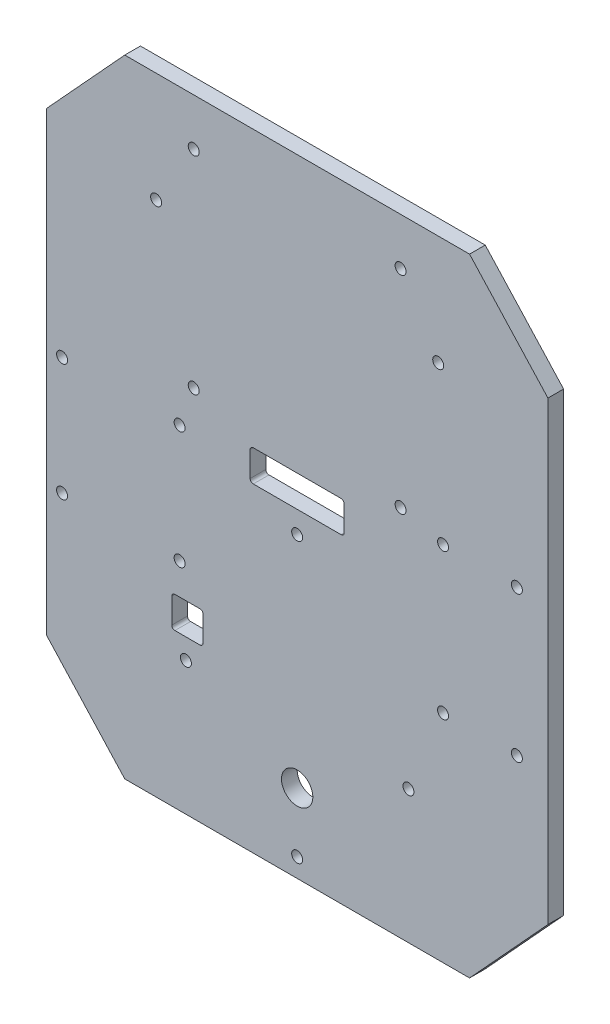
SolidWorks part; units mm, degrees
ref_plane "Plan de face" through (0, 0, 0) normal (1, 0, 0) x (0, 1, 0)
ref_plane "Plan de dessus" through (0, 0, 0) normal (0, 0, 1) x (0, 1, 0)
ref_plane "Plan de droite" through (0, 0, 0) normal (0, 1, 0) x (-1, 0, 0)
sketch "Esquisse1" plane through (0, 0, 0) normal (0, 0, 1) x (0, 1, 0)
  line L0 (0, 0) -> (-150.5414, 0) construction
  line L1 (-100, -80) -> (100, -80)
  line L2 (-100, -80) -> (-100, 80)
  line L3 (-100, 80) -> (100, 80)
  line L5 (-100, -80) -> (100, 80) construction
  line L6 (-100, 80) -> (100, -80) construction
  line L12 (-31, 38.8179) -> (-31, 42.3315) construction
  line L13 (-51, 40) -> (-41, 40)
  line L17 (-51, 40) -> (-51, 30)
  line L18 (-51, 30) -> (-41, 30)
  line L19 (-41, 40) -> (-41, 30)
  line L21 (-31.059, 37.5) -> (-30.571, 37.5) construction
  line L22 (-31, -46.5413) -> (-34.2714, -46.5413) construction
  line L28 (100, 80) -> (100, -80)
  line L30 (2, 15) -> (12, 15)
  line L31 (2, 15) -> (2, -15)
  line L32 (2, -15) -> (12, -15)
  line L33 (12, 15) -> (12, -15)
  circle A0 centre (-75, 0) radius 5
  circle A1 centre (-57.5, 35.5) radius 1.75
  circle A2 centre (-57.5, -35.5) radius 1.75
  circle A3 centre (65, 45) radius 1.75
  circle A4 centre (65, -45) radius 1.75
  circle A5 centre (-31, 37.5) radius 1.75
  circle A6 centre (-31, 75) radius 1.75
  circle A7 centre (6.5, 75) radius 1.75
  circle A8 centre (6.5, 37.5) radius 1.75
  circle A9 centre (-31, -46.5413) radius 1.75
  circle A10 centre (-31, -70.0913) radius 1.75
  circle A11 centre (15.5, -46.5413) radius 1.75
  circle A12 centre (15.5, -70.0913) radius 1.75
  circle A13 centre (-4.9993, 0) radius 1.75
  circle A16 centre (85, 33) radius 1.75
  circle A17 centre (85.0012, -33) radius 1.75
  circle A18 centre (19, 33) radius 1.75
  circle A19 centre (19.0012, -33) radius 1.75
  point P0 (0, 0)
  dimension "D3" = 10
  dimension "D9" = 3.5
  dimension "D10" = 35.5
  dimension "D11" = 17.5
  dimension "D5" = 3.5
  dimension "D6" = 45
  dimension "D7" = 15
  dimension "D16" = 37.5
  dimension "D17" = 37.5
  dimension "D18" = 37.5
  dimension "D19" = 3.5
  dimension "D20" = 3.5
  dimension "D21" = 3.5
  dimension "D22" = 3.5
  dimension "D23" = 10
  dimension "D24" = 5
  dimension "D25" = 3.5
  dimension "D26" = 3.5
  dimension "D27" = 3.5
  dimension "D28" = 3.5
  dimension "D29" = 46.5
  dimension "D30" = 46.5
  dimension "D31" = 23.55
  dimension "D32" = 23.55
  dimension "D35" = 3.5
  dimension "D36" = 3.5
  dimension "D41" = 66
  dimension "D42" = 66
  dimension "D47" = 3.5
  dimension "D48" = 3.5
  dimension "D50" = 66
  dimension "D52" = 33
  dimension "D33" = 14.9988
  dimension "D34" = 3.5
  dimension "D40" = 66
  dimension "D1" = 200
  dimension "D2" = 160
  dimension "D4" = 25
  dimension "D8" = 6.5
  dimension "D12" = 10
  dimension "D13" = 10
  dimension "D14" = 40
  dimension "D15" = 37.5
  dimension "D37" = 15
  dimension "D38" = 15
  dimension "D39" = 10
  dimension "D43" = 102
extrude "Boss.-Extru.1" add sketch "Esquisse1" along normal blind 5
fillet "Congé2" radius 1 8 edges at (-30, -51, 2.5) (-30, -41, 2.5) (-40, -41, 2.5) (-40, -51, 2.5) (15, 2, 2.5) (15, 12, 2.5) (-15, 12, 2.5) (-15, 2, 2.5)
sketch "Esquisse2" plane through (0, 0, 5) normal (0, 0, 1) x (1, 0, 0)
  line L0 (-110, 40) -> (0, 160)
  line L1 (0, 160) -> (110, 40)
  line L2 (110, 40) -> (110, -40)
  line L3 (110, -40) -> (0, -160)
  line L5 (0, -160) -> (-110, -40)
  line L6 (-110, -40) -> (-110, 40)
  line L14 (-573.5804, 598.1671) -> (-698.6982, -488.0825)
  line L15 (-80, 100) -> (-80, -100) construction
  line L16 (80, -100) -> (80, 100) construction
  line L17 (0, 70) -> (0, 33.5097) construction
  line L18 (-698.6982, -488.0825) -> (684.3, -647.3807)
  line L19 (0, 0) -> (-114.7759, 0) construction
  line L20 (684.3, -647.3807) -> (762.9047, 702.4319)
  line L21 (762.9047, 702.4319) -> (-573.5804, 598.1671)
  dimension "D1" = 160
  dimension "D2" = 160
  dimension "D3" = 40
  dimension "D4" = 40
  dimension "D5" = 40
  dimension "D6" = 40
  dimension "D7" = 110
extrude "Enlèv. mat.-Extru.1" cut sketch "Esquisse2" against normal through all
sketch "Esquisse3" plane through (0, 0, 0) normal (0, 0, 1) x (0, 1, 0)
  circle A0 centre (-94.0015, 0.004) radius 1.75
extrude "Trou cuve direction" cut sketch "Esquisse3" along normal through all
